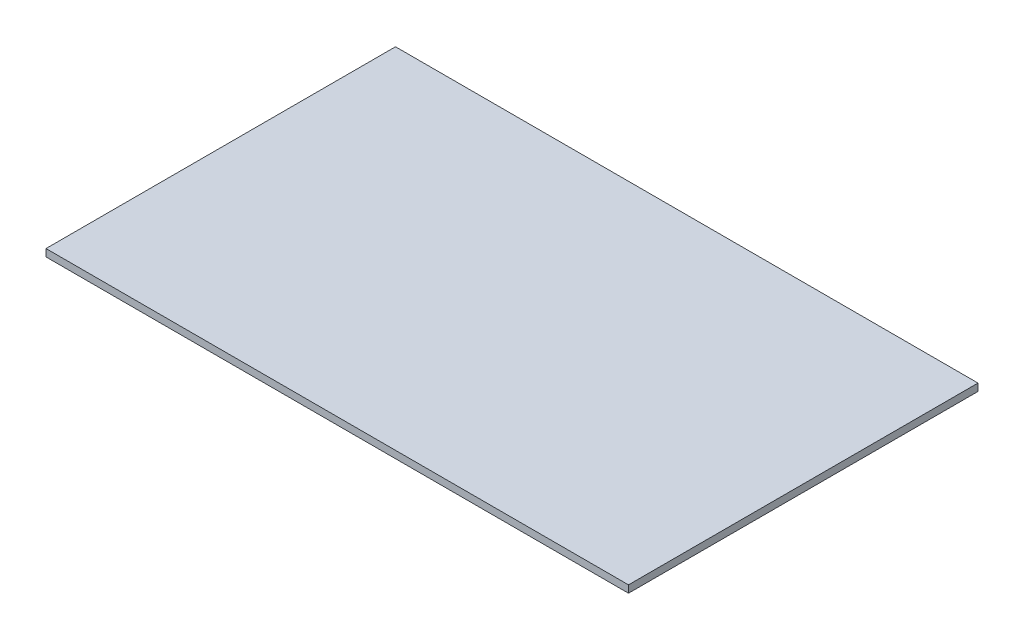
SolidWorks part; units mm, degrees
ref_plane "Front Plane" through (0, 0, 0) normal (0, 0, 1) x (1, 0, 0)
ref_plane "Top Plane" through (0, 0, 0) normal (0, 1, 0) x (1, 0, 0)
ref_plane "Right Plane" through (0, 0, 0) normal (1, 0, 0) x (0, 0, -1)
sketch "Sketch1" plane through (0, 0, 0) normal (0, 1, 0) x (1, 0, 0)
  line L1 (-254, -152.4) -> (254, -152.4)
  line L2 (-254, -152.4) -> (-254, 152.4)
  line L3 (-254, 152.4) -> (254, 152.4)
  line L4 (254, -152.4) -> (254, 152.4)
  line L5 (-254, -152.4) -> (254, 152.4) construction
  line L6 (-254, 152.4) -> (254, -152.4) construction
  point P0 (0, 0)
  dimension "D1" = 304.8
  dimension "D2" = 508
extrude "Boss-Extrude1" add sketch "Sketch1" along normal mid plane 6.35
